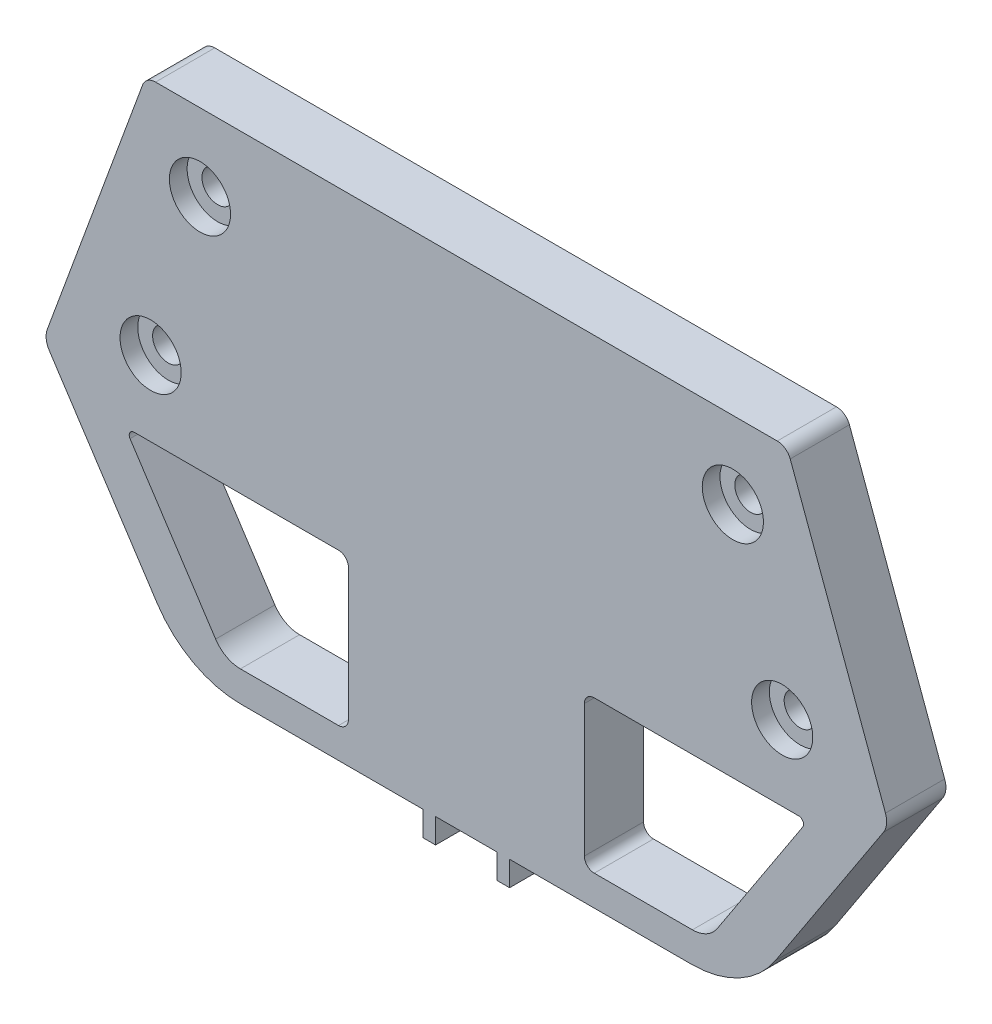
SolidWorks part; units mm, degrees
ref_plane "Front Plane" through (0, 0, 0) normal (0, 0, 1) x (1, 0, 0)
ref_plane "Top Plane" through (0, 0, 0) normal (0, 1, 0) x (1, 0, 0)
ref_plane "Right Plane" through (0, 0, 0) normal (1, 0, 0) x (0, 0, -1)
sketch "Sketch2" plane through (0, 0, 0) normal (0, 0, 1) x (1, 0, 0)
  line L0 (0, -44.7145) -> (0, 43.9236) construction
  line L3 (-53.9331, -0.3154) -> (-41.6738, 33.03)
  line L5 (-53.6746, -2.5826) -> (-39.7807, -23.8164)
  line L8 (-28.9986, -29.6465) -> (28.9986, -29.6465)
  line L9 (-40.005, 34.1945) -> (40.005, 34.1945)
  line L10 (53.6746, -2.5826) -> (39.7807, -23.8164)
  line L11 (53.9331, -0.3154) -> (41.6738, 33.03)
  arc A1 (-40.005, 34.1945) -> (-41.6738, 33.03) centre (-40.005, 32.4165) ccw
  arc A6 (-28.9986, -29.6465) -> (-39.7807, -23.8164) centre (-28.9986, -16.7614) cw
  arc A8 (-53.6746, -2.5826) -> (-53.9331, -0.3154) centre (-51.5491, -1.1919) cw
  arc A10 (53.6746, -2.5826) -> (53.9331, -0.3154) centre (51.5491, -1.1919) ccw
  arc A11 (28.9986, -29.6465) -> (39.7807, -23.8164) centre (28.9986, -16.7614) ccw
  arc A13 (40.005, 34.1945) -> (41.6738, 33.03) centre (40.005, 32.4165) cw
  point P4 (0, 57.6776)
  point P9 (0, 19.5776)
  point P12 (54.3738, -1.514)
  point P13 (0, -29.6465)
  point P19 (-35.9659, -29.6465)
  point P20 (0, -3.9055)
  point P28 (-54.3738, -1.514)
  point P33 (0, 34.1945)
  point P34 (35.9659, -29.6465)
  dimension "D2" = 1.778
  dimension "D3" = 12.8851
  dimension "D6" = 28.9986
  dimension "D4" = 2.54
  dimension "D7" = 35.9659
  dimension "D8" = 40.005
  dimension "D9" = 41.6738
  dimension "D10" = 51.5491
  dimension "D12" = 19.5776
  dimension "D13" = 32.4165
  dimension "D14" = 57.6776
extrude "Boss-Extrude1" add sketch "Sketch2" along normal blind 7.62
sketch "Sketch6" plane through (0, 0, 7.62) normal (0, 0, 1) x (1, 0, 0)
  line L0 (0, -25.1696) -> (0, 28.2164) construction
  line L3 (-43.2885, -7.1893) -> (-32.2734, -24.0235)
  line L4 (-53.6746, -2.5826) -> (-39.7807, -23.8164) construction
  line L5 (-54.0728, -1.4797) -> (0, -1.4797) construction
  line L6 (-42.7572, -6.2066) -> (-16.453, -6.2066)
  line L7 (-15.183, -7.4766) -> (-15.183, -24.4774)
  line L13 (-29.0853, -25.7474) -> (-16.453, -25.7474)
  line L14 (43.2885, -7.1893) -> (32.2734, -24.0235)
  line L17 (29.0853, -25.7474) -> (16.453, -25.7474)
  line L18 (15.183, -7.4766) -> (15.183, -24.4774)
  line L19 (42.7572, -6.2066) -> (16.453, -6.2066)
  line L20 (-11.43, -10.9992) -> (-11.43, -29.6465) construction
  line L21 (-28.9986, -29.6465) -> (28.9986, -29.6465) construction
  arc A3 (-53.9331, -0.3154) -> (-53.6746, -2.5826) centre (-51.5491, -1.1919) ccw construction
  arc A6 (-15.183, -7.4766) -> (-16.453, -6.2066) centre (-16.453, -7.4766) ccw
  arc A7 (-42.7572, -6.2066) -> (-43.2885, -7.1893) centre (-42.7572, -6.8416) ccw
  arc A12 (-29.0853, -25.7474) -> (-32.2734, -24.0235) centre (-29.0853, -21.9374) cw
  arc A13 (-15.183, -24.4774) -> (-16.453, -25.7474) centre (-16.453, -24.4774) cw
  arc A14 (42.7572, -6.2066) -> (43.2885, -7.1893) centre (42.7572, -6.8416) cw
  arc A15 (29.0853, -25.7474) -> (32.2734, -24.0235) centre (29.0853, -21.9374) ccw
  arc A16 (15.183, -24.4774) -> (16.453, -25.7474) centre (16.453, -24.4774) ccw
  arc A17 (15.183, -7.4766) -> (16.453, -6.2066) centre (16.453, -7.4766) cw
  dimension "D1" = 3.81
  dimension "D2" = 1.27
  dimension "D3" = 26.613
  dimension "D4" = 0.635
  dimension "D5" = 40.5153
  dimension "D6" = 54.1872
  dimension "D7" = 3.8991
extrude "Cut-Extrude4" cut sketch "Sketch6" against normal through all
sketch "Sketch8" plane through (0, 0, 7.62) normal (0, 0, 1) x (1, 0, 0)
  line L0 (0, 24.5882) -> (0, -31.804) construction
  line L1 (-16.453, -6.2066) -> (-42.7572, -6.2066) construction
  circle A0 centre (-40.64, 3.4454) radius 2.032
  circle A1 centre (-34.29, 24.2734) radius 2.032
  circle A2 centre (40.64, 3.4454) radius 2.032
  circle A3 centre (34.29, 24.2734) radius 2.032
  dimension "D1" = 4.064
  dimension "D2" = 4.064
  dimension "D3" = 40.64
  dimension "D4" = 34.29
  dimension "D5" = 9.652
  dimension "D6" = 30.48
extrude "Cut-Extrude6" cut sketch "Sketch8" against normal through all
sketch "Sketch9" plane through (0, -29.6465, 0) normal (0, -1, 0) x (1, 0, 0)
  line L0 (0, -14.4205) -> (0, 21.768) construction
  line L1 (-28.9986, 3.81) -> (28.9986, 3.81) construction
  line L2 (-28.9986, 7.62) -> (-28.9986, 0) construction
  line L3 (28.9986, 7.62) -> (28.9986, 0) construction
  circle A0 centre (0, 3.81) radius 2.032
  dimension "D1" = 4.064
extrude "Cut-Extrude7" cut sketch "Sketch9" against normal blind 25.4
sketch "Sketch11" plane through (0, 0, 7.62) normal (0, 0, 1) x (1, 0, 0)
  line L0 (0, 31.297) -> (0, -23.5528) construction
  circle A0 centre (-34.29, 24.2734) radius 3.937
  circle A1 centre (-40.64, 3.4454) radius 3.937
  circle A2 centre (40.64, 3.4454) radius 3.937
  circle A3 centre (34.29, 24.2734) radius 3.937
  dimension "D1" = 7.874
  dimension "D2" = 7.874
extrude "Cut-Extrude9" cut sketch "Sketch11" against normal blind 2.286
sketch "Sketch12" plane through (0, 0, 7.62) normal (0, 0, 1) x (1, 0, 0)
  line L0 (-28.9986, -29.6465) -> (28.9986, -29.6465) construction
  line L1 (-5.5563, -32.8215) -> (-3.9688, -32.8215)
  line L2 (-5.5563, -32.8215) -> (-5.5563, -29.6465)
  line L3 (-5.5563, -29.6465) -> (-3.9688, -29.6465)
  line L4 (-3.9688, -32.8215) -> (-3.9688, -29.6465)
  line L5 (-5.5563, -32.8215) -> (-3.9688, -29.6465) construction
  line L6 (-5.5563, -29.6465) -> (-3.9688, -32.8215) construction
  line L7 (-3.9688, -29.6465) -> (0, -29.6465) construction
  line L8 (5.5563, -32.8215) -> (3.9688, -32.8215)
  line L9 (5.5563, -32.8215) -> (5.5563, -29.6465)
  line L10 (5.5563, -29.6465) -> (3.9688, -29.6465)
  line L11 (3.9688, -32.8215) -> (3.9688, -29.6465)
  line L12 (5.5563, -32.8215) -> (3.9688, -29.6465) construction
  line L13 (5.5563, -29.6465) -> (3.9688, -32.8215) construction
  line L14 (0, -29.6465) -> (3.9688, -29.6465) construction
  point P0 (-4.7625, -31.234)
  point P7 (4.7625, -31.234)
  dimension "D1" = 7.9375
  dimension "D2" = 1.5875
  dimension "D3" = 3.175
extrude "Boss-Extrude2" add sketch "Sketch12" against normal up to surface (7.62 mm away) up to face at (-38.608, 3.4454, 0)
